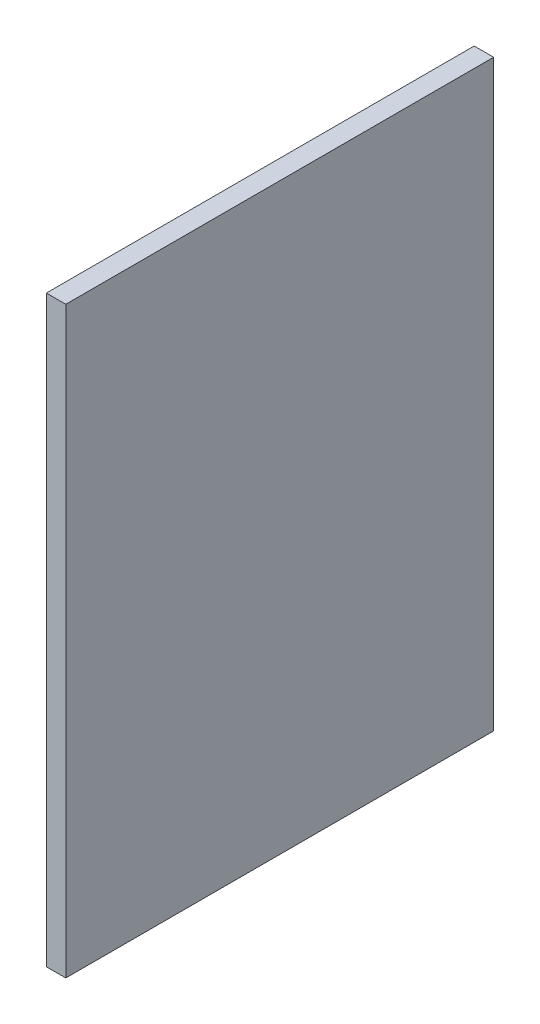
SolidWorks part; units mm, degrees
material "Glas"
ref_plane "Ebene vorne" through (0, 0, 0) normal (0, 0, 1) x (1, 0, 0)
ref_plane "Ebene oben" through (0, 0, 0) normal (0, 1, 0) x (1, 0, 0)
ref_plane "Ebene rechts" through (0, 0, 0) normal (1, 0, 0) x (0, 0, -1)
sketch "Skizze1" plane through (0, 0, 0) normal (1, 0, 0) x (0, 0, -1)
  line L1 (-55, 75) -> (55, 75)
  line L2 (-55, 75) -> (-55, -75)
  line L3 (-55, -75) -> (55, -75)
  line L4 (55, 75) -> (55, -75)
  line L5 (-55, 75) -> (55, -75) construction
  line L6 (-55, -75) -> (55, 75) construction
  point P0 (0, 0)
  dimension "D1" = 150
  dimension "D2" = 110
extrude "Aufsatz-Linear austragen1" add sketch "Skizze1" along normal blind 5
